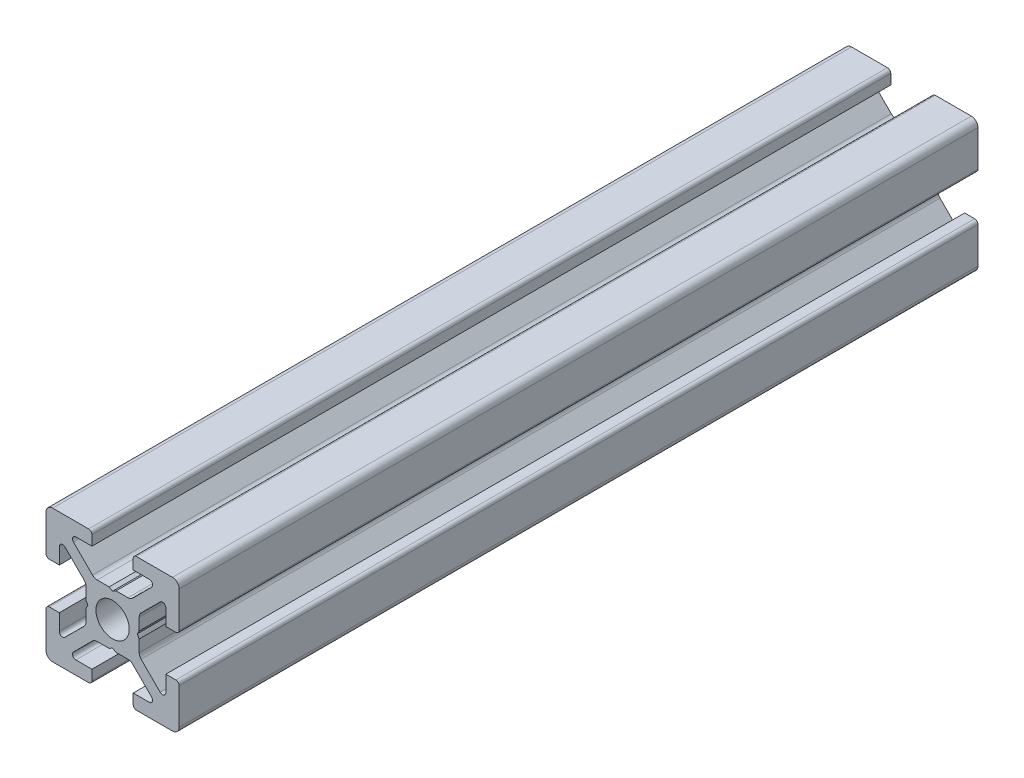
SolidWorks part; units mm, degrees
ref_plane "前视基准面" through (0, 0, 0) normal (0, 0, 1) x (1, 0, 0)
ref_plane "上视基准面" through (0, 0, 0) normal (0, 1, 0) x (1, 0, 0)
ref_plane "右视基准面" through (0, 0, 0) normal (1, 0, 0) x (0, 0, -1)
sketch "草图1" plane through (0, 0, 0) normal (0, 0, 1) x (1, 0, 0)
  line L0 (16.4868, 27.1233) -> (19.3403, 24.2698)
  line L1 (20.1939, 24.6233) -> (20.1939, 27.0434)
  line L2 (20.1939, 27.0434) -> (21.6939, 27.0434)
  line L3 (15.8939, 30.1434) -> (16.1939, 29.6238)
  line L4 (12.1939, 33.8434) -> (12.7135, 34.1434)
  line L5 (22.1939, 26.5434) -> (22.1939, 21.1434)
  line L6 (21.1939, 20.1434) -> (15.7939, 20.1434)
  line L7 (12.1939, 33.8434) -> (11.6743, 34.1434)
  line L8 (12.7135, 34.1434) -> (14.5069, 34.1434)
  line L9 (15.2939, 20.6434) -> (15.2939, 22.1434)
  line L10 (15.2939, 22.1434) -> (17.714, 22.1434)
  line L11 (18.0675, 22.997) -> (15.214, 25.8506)
  line L12 (14.5069, 26.1434) -> (12.7135, 26.1434)
  line L13 (9.1738, 25.8506) -> (6.3202, 22.997)
  line L14 (6.6738, 22.1434) -> (9.0939, 22.1434)
  line L15 (9.0939, 22.1434) -> (9.0939, 20.6434)
  line L16 (15.8939, 30.1434) -> (16.1939, 30.6631)
  line L17 (12.1939, 26.4434) -> (11.6743, 26.1434)
  line L18 (8.5939, 20.1434) -> (3.1939, 20.1434)
  line L19 (2.1939, 21.1434) -> (2.1939, 26.5434)
  line L20 (12.1939, 26.4434) -> (12.7135, 26.1434)
  line L21 (8.4939, 30.1434) -> (8.1939, 30.6631)
  line L22 (2.6939, 27.0434) -> (4.1939, 27.0434)
  line L23 (4.1939, 27.0434) -> (4.1939, 24.6233)
  line L24 (5.0474, 24.2698) -> (7.901, 27.1233)
  line L25 (8.1939, 27.8305) -> (8.1939, 29.6238)
  line L26 (7.901, 33.1635) -> (5.0474, 36.0171)
  line L27 (4.1939, 35.6635) -> (4.1939, 33.2434)
  line L28 (4.1939, 33.2434) -> (2.6939, 33.2434)
  line L29 (8.4939, 30.1434) -> (8.1939, 29.6238)
  line L30 (16.1939, 29.6238) -> (16.1939, 27.8305)
  line L31 (2.1939, 33.7434) -> (2.1939, 39.1434)
  line L32 (3.1939, 40.1434) -> (8.5939, 40.1434)
  line L33 (11.6743, 26.1434) -> (9.8809, 26.1434)
  line L34 (8.1939, 30.6631) -> (8.1939, 32.4564)
  line L35 (9.0939, 39.6434) -> (9.0939, 38.1434)
  line L36 (9.0939, 38.1434) -> (6.6738, 38.1434)
  line L37 (6.3202, 37.2899) -> (9.1738, 34.4363)
  line L38 (9.8809, 34.1434) -> (11.6743, 34.1434)
  line L39 (15.214, 34.4363) -> (18.0675, 37.2899)
  line L40 (17.714, 38.1434) -> (15.2939, 38.1434)
  line L41 (15.2939, 38.1434) -> (15.2939, 39.6434)
  line L44 (15.7939, 40.1434) -> (21.1939, 40.1434)
  line L45 (22.1939, 39.1434) -> (22.1939, 33.7434)
  line L48 (21.6939, 33.2434) -> (20.1939, 33.2434)
  line L49 (20.1939, 33.2434) -> (20.1939, 35.6635)
  line L50 (19.3403, 36.0171) -> (16.4868, 33.1635)
  line L51 (16.1939, 32.4564) -> (16.1939, 30.6631)
  circle A0 centre (12.1939, 30.1434) radius 2.5
  arc A1 (16.1939, 27.8305) -> (16.4868, 27.1233) centre (17.1939, 27.8305) ccw
  arc A2 (19.3403, 24.2698) -> (20.1939, 24.6233) centre (19.6939, 24.6233) ccw
  arc A3 (21.1939, 20.1434) -> (22.1939, 21.1434) centre (21.1939, 21.1434) ccw
  arc A4 (17.714, 22.1434) -> (18.0675, 22.997) centre (17.714, 22.6434) ccw
  arc A5 (15.214, 25.8506) -> (14.5069, 26.1434) centre (14.5069, 25.1434) ccw
  arc A6 (9.8809, 26.1434) -> (9.1738, 25.8506) centre (9.8809, 25.1434) ccw
  arc A7 (6.3202, 22.997) -> (6.6738, 22.1434) centre (6.6738, 22.6434) ccw
  arc A8 (2.1939, 21.1434) -> (3.1939, 20.1434) centre (3.1939, 21.1434) ccw
  arc A9 (4.1939, 24.6233) -> (5.0474, 24.2698) centre (4.6939, 24.6233) ccw
  arc A10 (7.901, 27.1233) -> (8.1939, 27.8305) centre (7.1939, 27.8305) ccw
  arc A11 (8.1939, 32.4564) -> (7.901, 33.1635) centre (7.1939, 32.4564) ccw
  arc A12 (5.0474, 36.0171) -> (4.1939, 35.6635) centre (4.6939, 35.6635) ccw
  arc A13 (3.1939, 40.1434) -> (2.1939, 39.1434) centre (3.1939, 39.1434) ccw
  arc A14 (6.6738, 38.1434) -> (6.3202, 37.2899) centre (6.6738, 37.6434) ccw
  arc A15 (9.1738, 34.4363) -> (9.8809, 34.1434) centre (9.8809, 35.1434) ccw
  arc A16 (14.5069, 34.1434) -> (15.214, 34.4363) centre (14.5069, 35.1434) ccw
  arc A17 (18.0675, 37.2899) -> (17.714, 38.1434) centre (17.714, 37.6434) ccw
  arc A18 (22.1939, 39.1434) -> (21.1939, 40.1434) centre (21.1939, 39.1434) ccw
  arc A19 (20.1939, 35.6635) -> (19.3403, 36.0171) centre (19.6939, 35.6635) ccw
  arc A20 (16.4868, 33.1635) -> (16.1939, 32.4564) centre (17.1939, 32.4564) ccw
  arc A21 (15.7939, 20.1434) -> (15.2939, 20.6434) centre (15.7939, 20.6434) cw
  arc A22 (9.0939, 20.6434) -> (8.5939, 20.1434) centre (8.5939, 20.6434) cw
  arc A23 (2.1939, 26.5434) -> (2.6939, 27.0434) centre (2.6939, 26.5434) cw
  arc A24 (2.6939, 33.2434) -> (2.1939, 33.7434) centre (2.6939, 33.7434) cw
  arc A25 (22.1939, 26.5434) -> (21.6939, 27.0434) centre (21.6939, 26.5434) ccw
  arc A26 (21.6939, 33.2434) -> (22.1939, 33.7434) centre (21.6939, 33.7434) ccw
  arc A27 (15.7939, 40.1434) -> (15.2939, 39.6434) centre (15.7939, 39.6434) ccw
  arc A28 (9.0939, 39.6434) -> (8.5939, 40.1434) centre (8.5939, 39.6434) ccw
  dimension "D1" = 0.5
  dimension "D2" = 4
extrude "凸台-拉伸1" add sketch "草图1" along normal blind 120
